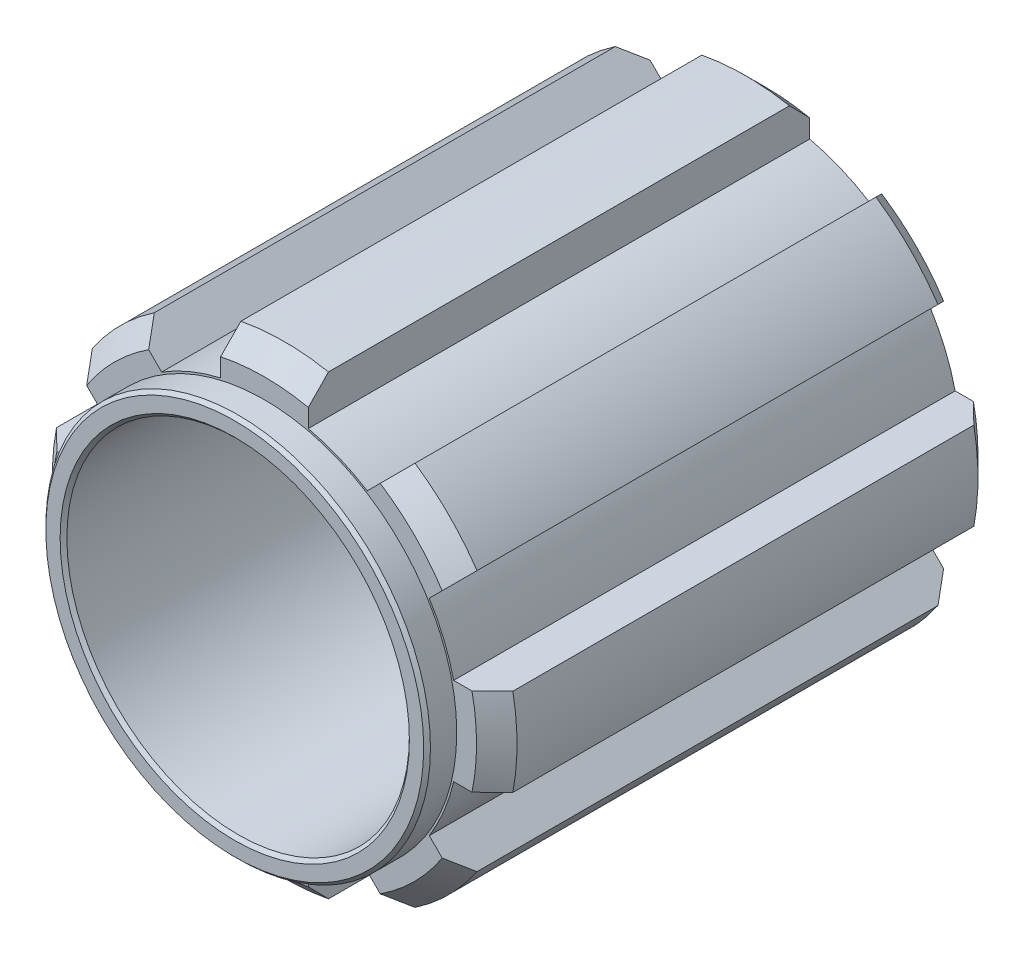
SolidWorks part; units mm, degrees
ref_plane "Front Plane" through (0, 0, 0) normal (0, 0, 1) x (1, 0, 0)
ref_plane "Top Plane" through (0, 0, 0) normal (0, 1, 0) x (1, 0, 0)
ref_plane "Right Plane" through (0, 0, 0) normal (1, 0, 0) x (0, 0, -1)
sketch "Sketch1" plane through (0, 0, 0) normal (0, 0, 1) x (1, 0, 0)
  circle A0 centre (0, 0) radius 12.695
  circle A1 centre (0, 0) radius 14.4
  dimension "D1" = 25.39
  dimension "D2" = 28.8
extrude "Boss-Extrude1" add sketch "Sketch1" along normal blind 39.37
sketch "Sketch2" plane through (0, 0, 39.37) normal (0, 0, 1) x (1, 0, 0)
  line L0 (-3.25, 16.9156) -> (-3.25, 14.0285)
  line L1 (0, 0) -> (0, 4.1131) construction
  line L2 (3.25, 16.9156) -> (3.25, 14.0285)
  arc A2 (3.25, 14.0285) -> (-3.25, 14.0285) centre (0, 0) ccw
  arc A3 (3.25, 16.9156) -> (-3.25, 16.9156) centre (0, 0) ccw
  circle A4 centre (0, 0) radius 14.4 construction
  dimension "D3" = 17.225
  dimension "D1" = 6.5
extrude "Boss-Extrude2" add sketch "Sketch2" against normal up to surface (39.37 mm away) up to face at (14.4, 0, 0)
pattern_circular "CirPattern1" count 8 over 360 about axis through (0, 0, 0) along (0, 0, 1) of "Boss-Extrude2"
sketch "Sketch3" plane through (0, 0, 39.37) normal (0, 0, 1) x (1, 0, 0)
  circle A0 centre (0, 0) radius 14.255
  dimension "D1" = 28.51
extrude "Cut-Extrude1" cut sketch "Sketch3" against normal blind 2.2 flip side to cut
sketch "Sketch5" plane through (0, 0, 0) normal (1, 0, 0) x (0, 0, -1)
  line L0 (-35.67, 17.225) -> (-37.17, 15.725)
  line L1 (0, 17.225) -> (-37.17, 17.225) construction
  line L2 (-37.17, 16.9156) -> (-37.17, 14.0285) construction
  line L3 (-37.17, 15.725) -> (-37.17, 17.225)
  line L4 (-37.17, 17.225) -> (-37.17, 16.9156) construction
  line L5 (-37.17, 17.225) -> (-35.67, 17.225)
  line L6 (0, 17.225) -> (-1.5, 17.225)
  line L7 (0, 16.9156) -> (0, 17.225) construction
  line L8 (-1.5, 17.225) -> (0, 15.725)
  line L10 (0, 15.725) -> (0, 17.225)
  line L11 (0, 16.9156) -> (0, 14.0285) construction
  line L12 (0, 0) -> (10.6164, 0) construction
  dimension "D1" = 1.5
  dimension "D2" = 1.5
  dimension "D3" = 1.5
  dimension "D4" = 1.5
revolve "Cut-Revolve1" cut sketch "Sketch5" angle 360 about L12
sketch "Sketch6" plane through (0, 0, 0) normal (0, 0, -1) x (-1, 0, 0)
  line L0 (-3.075, -9.525) -> (-3.075, -12.317)
  line L1 (0, 0) -> (0, 3.7952) construction
  line L2 (3.075, -9.525) -> (3.075, -12.317)
  line L3 (-3.075, -9.525) -> (3.075, -9.525)
  circle A0 centre (0, 0) radius 12.695 construction
  arc A2 (-3.25, -16.9156) -> (3.25, -16.9156) centre (0, 0) ccw construction
  arc A3 (-3.075, -12.317) -> (3.075, -12.317) centre (0, 0) ccw
  dimension "D1" = 6.15
  dimension "D2" = 7.7
  dimension "D3" = 22.22
sketch "Sketch8" plane through (0, 0, 0) normal (0, 1, 0) x (1, 0, 0)
  line L0 (-13.195, 0) -> (-12.695, -0.5)
  line L1 (-14.0285, 0) -> (-15.3855, 0) construction
  line L2 (-12.695, -0.5) -> (-12.695, 0)
  line L3 (12.695, 0) -> (-12.695, 0) construction
  line L5 (-12.695, 0) -> (-13.195, 0)
  line L6 (-12.695, 0) -> (-12.695, -39.37) construction
  line L7 (-12.695, -0.5) -> (-8.195, -5)
  line L8 (-8.195, -5) -> (-8.195, 0)
  line L9 (-8.5811, 0) -> (-13.1773, 0) construction
  line L10 (-8.195, 0) -> (-12.695, 0)
  line L11 (0, 0) -> (0, 3.5879) construction
  dimension "D1" = 0.5
  dimension "D2" = 5
  dimension "D3" = 0.5
revolve "Cut-Revolve2" cut sketch "Sketch8" angle 360 about L11
chamfer "Chamfer2" distance 0.25 angle 45 2 edges at (12.695, 0, 39.37) (14.255, 0, 39.37)
